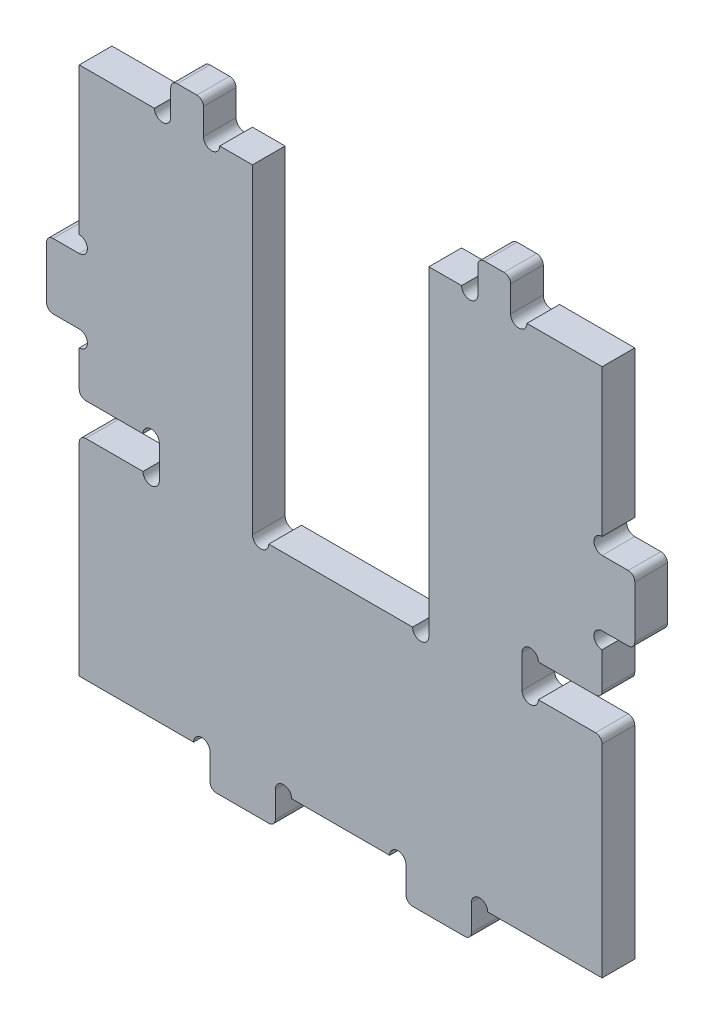
SolidWorks part; units mm, degrees
ref_plane "정면" through (0, 0, 0) normal (0, 0, 1) x (1, 0, 0)
ref_plane "윗면" through (0, 0, 0) normal (0, 1, 0) x (1, 0, 0)
ref_plane "우측면" through (0, 0, 0) normal (1, 0, 0) x (0, 0, -1)
sketch "스케치1" plane through (0, 0, 0) normal (0, 0, 1) x (1, 0, 0)
  line L0 (-66, 5) -> (-84, 5) construction
  line L1 (-5, 86) -> (-85, 86)
  line L2 (-5, 86) -> (-5, 5)
  line L3 (-5, 5) -> (-85, 5)
  line L4 (-85, 86) -> (-85, 5)
  line L5 (-85, 0) -> (-85, 18.45) construction
  line L6 (-18, 86) -> (-6, 86) construction
  line L7 (-5, 72.55) -> (-5, 91) construction
extrude "보스-돌출1" add sketch "스케치1" against normal blind 5
sketch "스케치2" plane through (0, 0, 0) normal (0, 0, 1) x (1, 0, 0)
  line L0 (-5, 5) -> (-5, 86) construction
  line L1 (-17.25, 42) -> (-5, 42)
  line L2 (-17.25, 42) -> (-17.25, 37)
  line L3 (-17.25, 37) -> (-5, 37)
  line L4 (-5, 42) -> (-5, 37)
  line L5 (-5, 37) -> (-17.25, 37) construction
  line L6 (-85, 86) -> (-85, 5) construction
  line L8 (-5, 86) -> (-85, 86) construction
  line L9 (-58.5, 37) -> (-31.5, 37)
  line L10 (-58.5, 37) -> (-58.5, 86)
  line L11 (-72.75, 42) -> (-85, 42)
  line L12 (-72.75, 42) -> (-72.75, 37)
  line L13 (-72.75, 37) -> (-85, 37)
  line L14 (-85, 42) -> (-85, 37)
  line L15 (-85, 37) -> (-88, 37) construction
  line L16 (-58.5, 86) -> (-31.5, 86)
  line L17 (-31.5, 37) -> (-31.5, 86)
extrude "컷-돌출1" cut sketch "스케치2" against normal blind 10
sketch "스케치5" plane through (0, 0, 0) normal (0, 0, 1) x (1, 0, 0)
  line L0 (-85, 5) -> (-5, 5) construction
  line L1 (-25, 5) -> (-35, 5)
  line L2 (-25, 5) -> (-25, 0)
  line L3 (-25, 0) -> (-35, 0)
  line L4 (-35, 5) -> (-35, 0)
  line L5 (-35, 0) -> (-55, 0) construction
  line L6 (-5, 42) -> (-5, 86) construction
  line L7 (-55, 5) -> (-65, 5)
  line L8 (-55, 5) -> (-55, 0)
  line L9 (-55, 0) -> (-65, 0)
  line L10 (-65, 5) -> (-65, 0)
  line L11 (-5, 51) -> (0, 51)
  line L12 (-5, 51) -> (-5, 61)
  line L13 (-5, 61) -> (0, 61)
  line L14 (0, 51) -> (0, 61)
  line L15 (0, 21.55) -> (0, 51) construction
  line L16 (-85, 86) -> (-85, 42) construction
  line L17 (-85, 51) -> (-90, 51)
  line L18 (-85, 51) -> (-85, 61)
  line L19 (-85, 61) -> (-90, 61)
  line L20 (-90, 51) -> (-90, 61)
  line L21 (-90, 21.55) -> (-90, 51) construction
  line L22 (-58.5, 86) -> (-85, 86) construction
  line L23 (-66, 86) -> (-71, 86)
  line L24 (-66, 86) -> (-66, 91)
  line L25 (-66, 91) -> (-71, 91)
  line L26 (-71, 86) -> (-71, 91)
  line L27 (-24, 91) -> (-66, 91) construction
  line L28 (-5, 86) -> (-31.5, 86) construction
  line L30 (-58.5, 88.5) -> (-58.5, 86) construction
  line L32 (-31.5, 88.5) -> (-31.5, 86) construction
  line L33 (-71, 88.5) -> (-85, 88.5) construction
  line L34 (-24, 86) -> (-19, 86)
  line L35 (-24, 86) -> (-24, 91)
  line L36 (-24, 91) -> (-19, 91)
  line L37 (-19, 86) -> (-19, 91)
  line L38 (-85, 72.55) -> (-85, 91) construction
  line L39 (-19, 88.5) -> (-5, 88.5) construction
  line L40 (-5, 72.55) -> (-5, 91) construction
  line L41 (-65, 2.5) -> (-85, 2.5) construction
  line L42 (-85, 0) -> (-85, 18.45) construction
  line L43 (-25, 2.5) -> (-5, 2.5) construction
  line L44 (-5, 0) -> (-5, 18.45) construction
  dimension "D1" = 5
  dimension "D2" = 5
  dimension "D3" = 25
  dimension "D4" = 10
  dimension "D5" = 10
  dimension "D6" = 10
  dimension "D7" = 20
  dimension "D8" = 14
  dimension "D9" = 14
extrude "보스-돌출2" add sketch "스케치5" against normal blind 5
fillet "필렛1" radius 1 16 edges at (-19, 91, -2.5) (-66, 91, -2.5) (-71, 91, -2.5) (-24, 91, -2.5) (-65, 0, -2.5) (-35, 0, -2.5) (-55, 0, -2.5) (-25, 0, -2.5) (-5, 37, -2.5) (-5, 42, -2.5) (0, 61, -2.5) (0, 51, -2.5) (-85, 37, -2.5) (-85, 42, -2.5) (-90, 51, -2.5) (-90, 61, -2.5)
sketch "스케치6" plane through (0, 0, 0) normal (0, 0, 1) x (1, 0, 0)
  line L0 (-58.5, 37) -> (-31.5, 37) construction
  line L1 (-72.75, 42) -> (-84, 42) construction
  line L2 (-84, 37) -> (-72.75, 37) construction
  line L3 (-6, 42) -> (-17.25, 42) construction
  line L4 (-17.25, 37) -> (-6, 37) construction
  line L5 (-5, 43) -> (-5, 51) construction
  line L6 (-5, 61) -> (-5, 86) construction
  line L7 (-85, 86) -> (-85, 61) construction
  line L8 (-85, 51) -> (-85, 43) construction
  line L9 (-85, 5) -> (-65, 5) construction
  line L10 (-55, 5) -> (-35, 5) construction
  line L11 (-25, 5) -> (-5, 5) construction
  line L12 (-71, 86) -> (-85, 86) construction
  line L13 (-58.5, 86) -> (-66, 86) construction
  line L14 (-24, 86) -> (-31.5, 86) construction
  line L15 (-5, 86) -> (-19, 86) construction
  circle A0 centre (-32.75, 37) radius 1.25
  circle A1 centre (-57.25, 37) radius 1.25
  circle A2 centre (-74, 42) radius 1.25
  circle A3 centre (-74, 37) radius 1.25
  circle A4 centre (-16, 42) radius 1.25
  circle A5 centre (-16, 37) radius 1.25
  circle A6 centre (-5, 49.75) radius 1.25
  circle A7 centre (-5, 62.25) radius 1.25
  circle A8 centre (-85, 62.25) radius 1.25
  circle A9 centre (-85, 49.75) radius 1.25
  circle A10 centre (-66.25, 5) radius 1.25
  circle A11 centre (-53.75, 5) radius 1.25
  circle A12 centre (-36.25, 5) radius 1.25
  circle A13 centre (-23.75, 5) radius 1.25
  circle A14 centre (-72.25, 86) radius 1.25
  circle A15 centre (-64.75, 86) radius 1.25
  circle A16 centre (-25.25, 86) radius 1.25
  circle A17 centre (-17.75, 86) radius 1.25
  dimension "D1" = 2.5
extrude "컷-돌출4" cut sketch "스케치6" against normal blind 10
